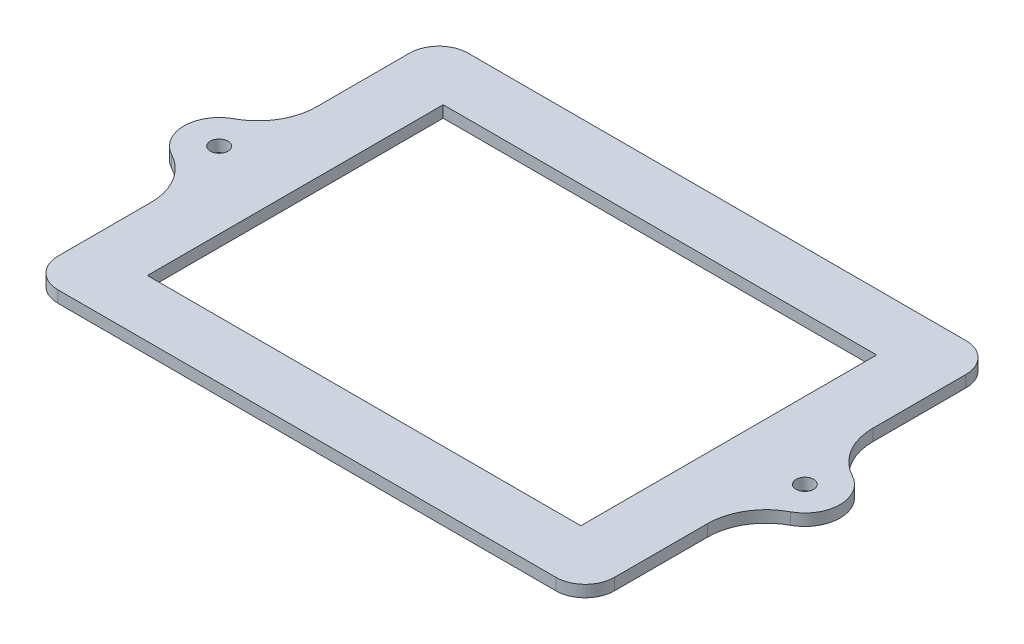
SolidWorks part; units mm, degrees
material "ABS"
ref_plane "Front Plane" through (0, 0, 0) normal (0, 0, 1) x (1, 0, 0)
ref_plane "Top Plane" through (0, 0, 0) normal (0, 1, 0) x (1, 0, 0)
ref_plane "Right Plane" through (0, 0, 0) normal (1, 0, 0) x (0, 0, -1)
sketch "Sketch2" plane through (0, 0, 0) normal (0, 1, 0) x (1, 0, 0)
  line L0 (0, 35) -> (0, 25.25) construction
  line L1 (-37, 25.25) -> (37, 25.25)
  line L2 (-37, 25.25) -> (-37, -25.25)
  line L3 (-37, -25.25) -> (37, -25.25)
  line L4 (37, 25.25) -> (37, -25.25)
  line L5 (-47.5, 35) -> (47.5, 35)
  line L6 (-47.5, 35) -> (-47.5, 5.4544)
  line L7 (-47.5, -35) -> (47.5, -35)
  line L8 (47.5, 35) -> (47.5, 5.4544)
  line L9 (0, 25.25) -> (0, 0) construction
  line L10 (0, 0) -> (0, -25.25) construction
  line L11 (0, -25.25) -> (0, -35) construction
  line L12 (-50, 0) -> (0, 0) construction
  line L13 (0, 0) -> (50, 0) construction
  line L14 (-47.5, -5.4544) -> (-47.5, -35)
  line L15 (47.5, -5.4544) -> (47.5, -35)
  arc A0 (-47.5, 5.4544) -> (-47.5, -5.4544) centre (-50, 0) ccw
  arc A1 (47.5, -5.4544) -> (47.5, 5.4544) centre (50, 0) ccw
  circle A2 centre (-50, 0) radius 1.5
  circle A3 centre (50, 0) radius 1.5
  dimension "D7" = 12
  dimension "D9" = 3
  dimension "D1" = 70
  dimension "D2" = 9.75
  dimension "D3" = 95
  dimension "D5" = 50.5
  dimension "D6" = 74
  dimension "D8" = 100
extrude "Boss-Extrude1" add sketch "Sketch2" along normal blind 2
fillet "Fillet1" radius 5 4 edges at (-47.5, 1, -35) (47.5, 1, -35) (47.5, 1, 35) (-47.5, 1, 35)
fillet "Fillet2" radius 10 4 edges at (-47.5, 1, -5.4544) (-47.5, 1, 5.4544) (47.5, 1, -5.4544) (47.5, 1, 5.4544)
